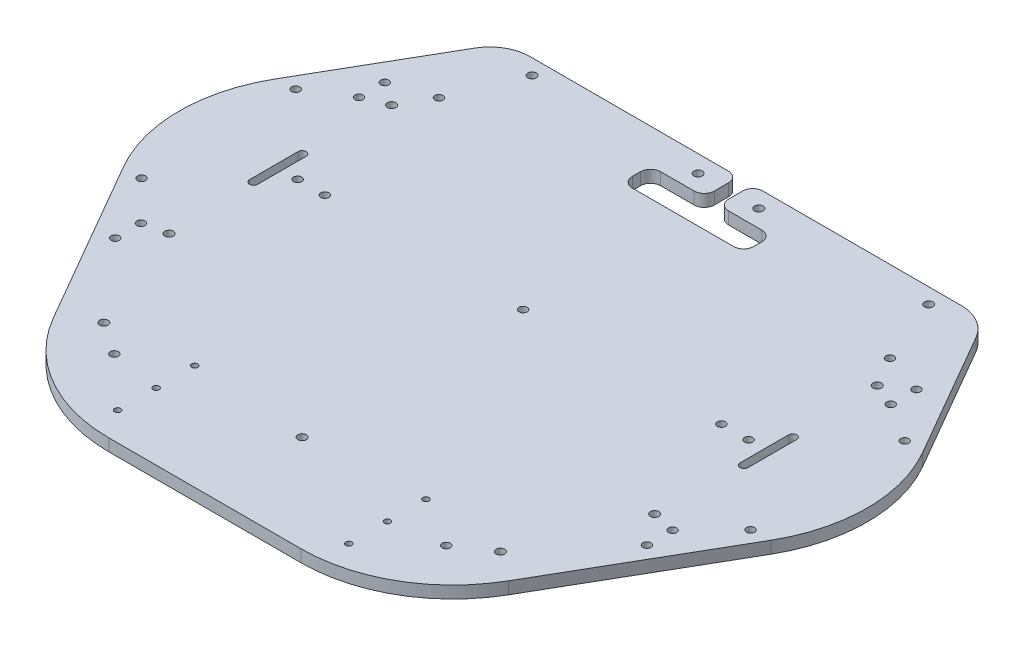
SolidWorks part; units mm, degrees
ref_plane "Plano frontal" through (0, 0, 0) normal (0, 0, 1) x (1, 0, 0)
ref_plane "Plano superior" through (0, 0, 0) normal (0, 1, 0) x (1, 0, 0)
ref_plane "Plano direito" through (0, 0, 0) normal (1, 0, 0) x (0, 0, -1)
ref_plane "Plano1" through (0, 6, 0) normal (0, 1, 0) x (1, 0, 0)
sketch "Esboço1" plane through (0, 6, 0) normal (0, 1, 0) x (1, 0, 0)
  line L0 (123.22, 12) -> (123.22, -12)
  line L1 (119.22, -12) -> (119.22, 12)
  line L2 (-123.22, -12) -> (-123.22, 12)
  line L3 (-119.22, 12) -> (-119.22, -12)
  line L4 (-3.5, 98) -> (-3.5, 105)
  line L5 (-8.5, 110) -> (-106.547, 110)
  line L6 (-123.8675, 100) -> (-159.9519, 37.5)
  line L7 (-159.9519, -37.5) -> (-112.4519, -119.7724)
  line L8 (-47.5, -157.2724) -> (47.5, -157.2724)
  line L9 (112.4519, -119.7724) -> (159.9519, -37.5)
  line L10 (159.9519, 37.5) -> (123.8675, 100)
  line L11 (106.547, 110) -> (8.5, 110)
  line L12 (3.5, 105) -> (3.5, 98)
  line L13 (8.5, 93) -> (25, 93)
  line L14 (30, 88) -> (30, 84)
  line L15 (25, 79) -> (-25, 79)
  line L16 (-30, 84) -> (-30, 88)
  line L17 (-25, 93) -> (-8.5, 93)
  arc A0 (119.22, 12) -> (123.22, 12) centre (121.22, 12) cw
  arc A1 (123.22, -12) -> (119.22, -12) centre (121.22, -12) cw
  arc A2 (-119.22, -12) -> (-123.22, -12) centre (-121.22, -12) cw
  arc A3 (-123.22, 12) -> (-119.22, 12) centre (-121.22, 12) cw
  circle A4 centre (-82, -120) radius 2
  circle A5 centre (82, -120) radius 2
  circle A6 centre (150.5, -38.1) radius 2
  circle A7 centre (150.5, 38.1) radius 2
  circle A8 centre (-150.5, -38.1) radius 2
  circle A9 centre (-150.5, 38.1) radius 2
  circle A10 centre (15, 101.5) radius 2.1
  circle A11 centre (98, 102.4382) radius 2.1
  circle A12 centre (-15, 101.5) radius 2.1
  circle A13 centre (131.4, -57.5) radius 2
  circle A14 centre (-131.4, -57.5) radius 2
  circle A15 centre (131.4, 63) radius 2
  circle A16 centre (-131.4, 63) radius 2
  circle A17 centre (131.4, -70.2) radius 2
  circle A18 centre (-131.4, -70.2) radius 2
  circle A19 centre (131.4, 50.3) radius 2
  circle A20 centre (-131.4, 50.3) radius 2
  circle A21 centre (120, 55) radius 2.1
  circle A22 centre (-120, 55) radius 2.1
  circle A23 centre (-120, -55) radius 2.1
  circle A24 centre (120, -55) radius 2.1
  circle A25 centre (111.4552, 0) radius 2
  circle A26 centre (111.4552, 69.85) radius 2
  circle A27 centre (-111.4552, 0) radius 2
  circle A28 centre (-111.4552, 69.85) radius 2
  circle A29 centre (-97.9932, 0) radius 2
  circle A30 centre (97.9932, 0) radius 2
  circle A31 centre (0, 0) radius 2
  circle A32 centre (98, -109.22) radius 2.1
  circle A33 centre (-98, -109.22) radius 2.1
  circle A34 centre (0, -109.22) radius 2.1
  circle A35 centre (-98, 102.4382) radius 2.1
  arc A36 (-3.5, 105) -> (-8.5, 110) centre (-8.5, 105) ccw
  arc A37 (-106.547, 110) -> (-123.8675, 100) centre (-106.547, 90) ccw
  arc A38 (-159.9519, 37.5) -> (-159.9519, -37.5) centre (-95, 0) ccw
  arc A39 (-112.4519, -119.7724) -> (-47.5, -157.2724) centre (-47.5, -82.2724) ccw
  arc A40 (47.5, -157.2724) -> (112.4519, -119.7724) centre (47.5, -82.2724) ccw
  arc A41 (159.9519, -37.5) -> (159.9519, 37.5) centre (95, 0) ccw
  arc A42 (123.8675, 100) -> (106.547, 110) centre (106.547, 90) ccw
  arc A43 (8.5, 110) -> (3.5, 105) centre (8.5, 105) ccw
  arc A44 (3.5, 98) -> (8.5, 93) centre (8.5, 98) ccw
  arc A45 (25, 93) -> (30, 88) centre (25, 88) cw
  arc A46 (30, 84) -> (25, 79) centre (25, 84) cw
  arc A47 (-25, 79) -> (-30, 84) centre (-25, 84) cw
  arc A48 (-30, 88) -> (-25, 93) centre (-25, 88) cw
  arc A49 (-8.5, 93) -> (-3.5, 98) centre (-8.5, 98) ccw
extrude "Ressalto-extrusão1" add sketch "Esboço1" against normal blind 6
sketch "Esboço3" plane through (0, 6, 0) normal (0, 1, 0) x (1, 0, 0)
  line L0 (0, -157.2724) -> (0, -143.2724) construction
  line L1 (-47.5, -157.2724) -> (47.5, -157.2724) construction
  line L2 (-57.15, -143.2724) -> (57.15, -143.2724) construction
  circle A0 centre (-57.15, -143.2724) radius 1.5
  circle A1 centre (57.15, -143.2724) radius 1.5
  circle A2 centre (-57.15, -124.2224) radius 1.5
  circle A3 centre (57.15, -124.2224) radius 1.5
  circle A4 centre (-57.15, -105.1724) radius 1.5
  circle A5 centre (57.15, -105.1724) radius 1.5
  dimension "D3" = 3
  dimension "D1" = 57.15
  dimension "D2" = 14
extrude "Corte-extrusão1" cut sketch "Esboço3" against normal through all
